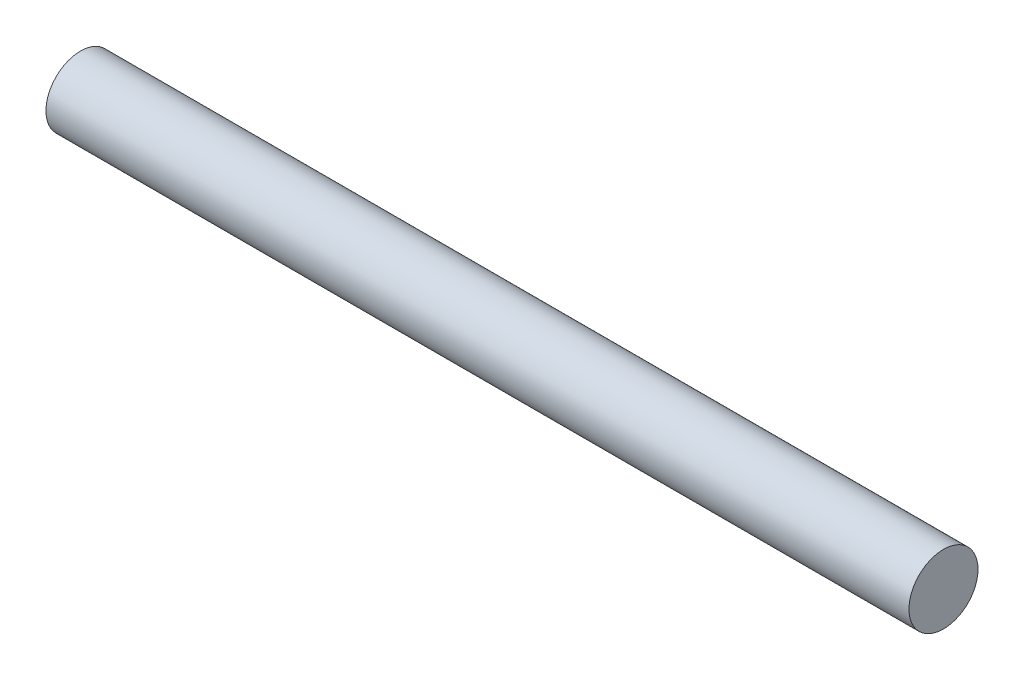
SolidWorks part; units mm, degrees
ref_plane "Front Plane" through (0, 0, 0) normal (0, 0, 1) x (1, 0, 0)
ref_plane "Top Plane" through (0, 0, 0) normal (0, 1, 0) x (1, 0, 0)
ref_plane "Right Plane" through (0, 0, 0) normal (1, 0, 0) x (0, 0, -1)
sketch "Sketch1" plane through (0, 0, 0) normal (1, 0, 0) x (0, 0, -1)
  circle A0 centre (0, 0) radius 4
  dimension "D1" = 8
extrude "Boss-Extrude1" add sketch "Sketch1" along normal blind 100
